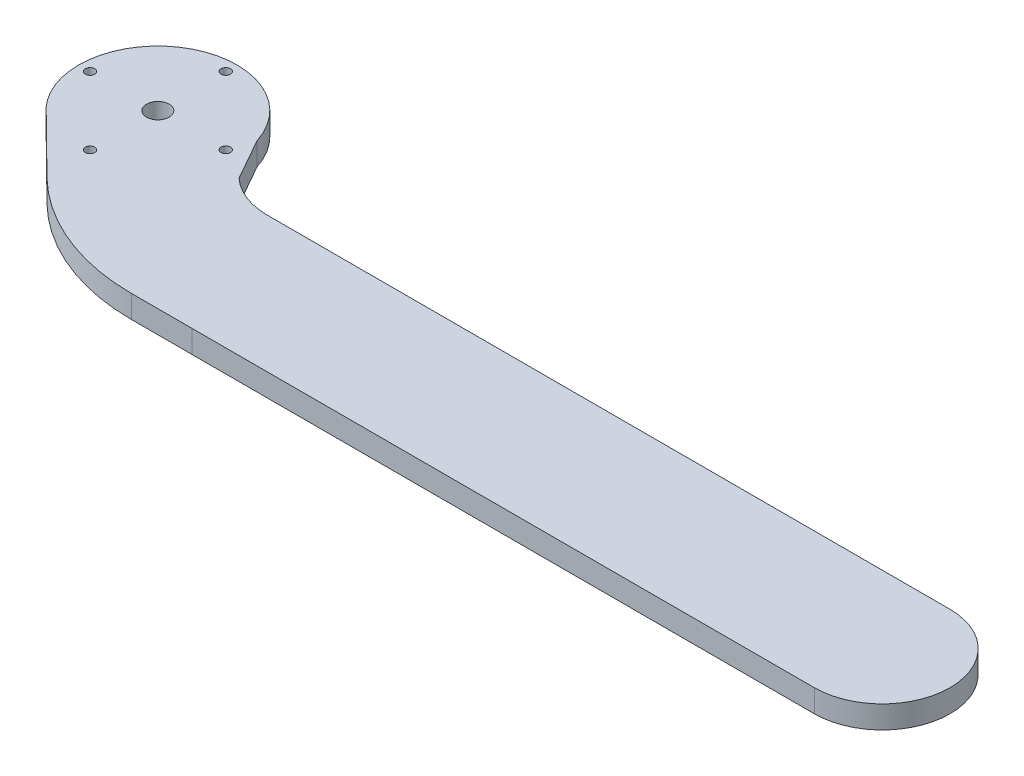
SolidWorks part; units mm, degrees
ref_plane "Front Plane" through (0, 0, 0) normal (0, 0, 1) x (1, 0, 0)
ref_plane "Top Plane" through (0, 0, 0) normal (0, 1, 0) x (1, 0, 0)
ref_plane "Right Plane" through (0, 0, 0) normal (1, 0, 0) x (0, 0, -1)
sketch "Sketch2" plane through (0, 0, 0) normal (0, 1, 0) x (1, 0, 0)
  line L0 (-224.2281, 94.1612) -> (85.2758, 94.1612)
  line L2 (85.2758, 34.1612) -> (-189.7242, 34.1612)
  line L3 (-216.6748, 94.1629) -> (-224.2281, 94.1612)
  line L9 (-216.6785, 34.1629) -> (-189.7242, 34.1612)
  line L10 (-279.3317, 59.5573) -> (-303.3685, 83.2864)
  line L11 (-236.8846, 101.9933) -> (-247.3338, 120.4702)
  arc A1 (85.2758, 34.1612) -> (85.2758, 94.1612) centre (85.2758, 64.1612) ccw
  arc A19 (-236.8846, 101.9933) -> (-216.6748, 94.1629) centre (-216.6729, 124.1629) ccw
  arc A20 (-279.3317, 59.5573) -> (-216.6785, 34.1629) centre (-216.6729, 124.1629) ccw
  arc A22 (-247.3338, 120.4702) -> (-303.3685, 83.2864) centre (-280.7224, 109.9726) ccw
  point P16 (-250.4801, 40.7538)
  dimension "D1" = 30
  dimension "D2" = 60
  dimension "D3" = 70
  dimension "D4" = 275
extrude "Boss-Extrude1" add sketch "Sketch2" along normal blind 10
sketch "Sketch3" plane through (0, 10, 0) normal (0, 1, 0) x (1, 0, 0)
  circle A0 centre (-280.7224, 109.9726) radius 5
  circle A1 centre (-280.7224, 139.9726) radius 2.1
  circle A2 centre (-310.7224, 109.9726) radius 2.1
  circle A3 centre (-280.7224, 79.9726) radius 2.1
  circle A4 centre (-250.7224, 109.9726) radius 2.1
  point P14 (-280.7224, 109.9726)
  dimension "D1" = 10
  dimension "D2" = 4.2
  dimension "D3" = 30
  dimension "D4" = 4
extrude "Cut-Extrude1" cut sketch "Sketch3" against normal blind 10
